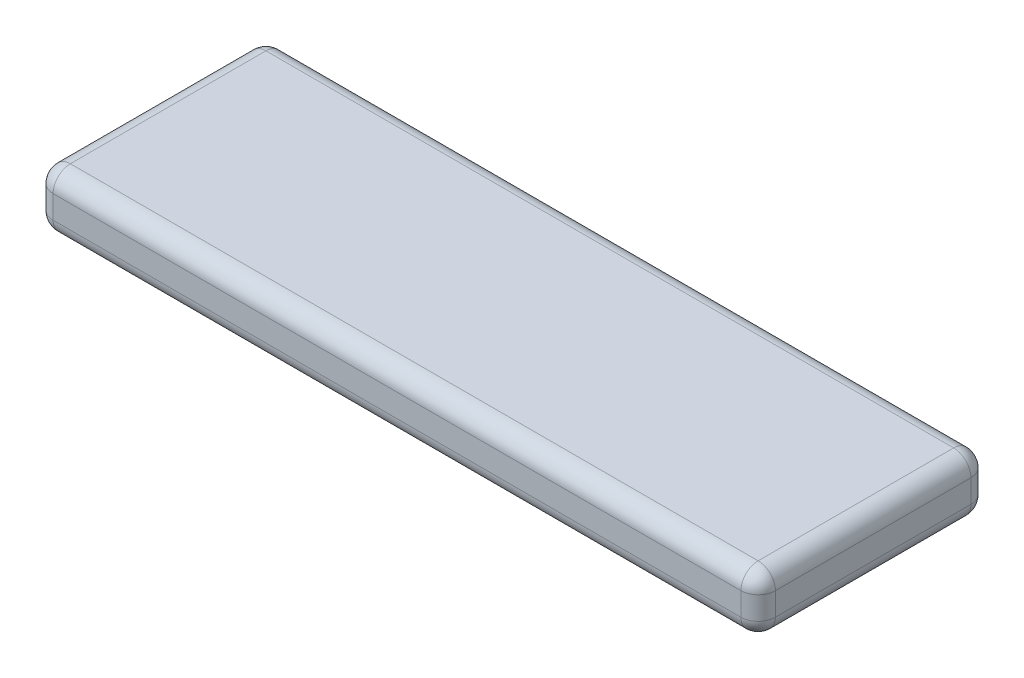
SolidWorks part; units mm, degrees
ref_plane "Front Plane" through (0, 0, 0) normal (0, 0, 1) x (1, 0, 0)
ref_plane "Top Plane" through (0, 0, 0) normal (0, 1, 0) x (1, 0, 0)
ref_plane "Right Plane" through (0, 0, 0) normal (1, 0, 0) x (0, 0, -1)
sketch "Sketch1" plane through (0, 0, 0) normal (0, 1, 0) x (1, 0, 0)
  line L1 (0, 0) -> (1256, 0)
  line L2 (0, 0) -> (0, 400)
  line L3 (0, 400) -> (1256, 400)
  line L4 (1256, 0) -> (1256, 400)
  dimension "D1" = 1256
  dimension "D2" = 400
extrude "Boss-Extrude1" add sketch "Sketch1" along normal blind 100
fillet "Fillet1" radius 30 12 edges at (0, 0, -200) (0, 50, -400) (628, 0, -400) (0, 50, 0) (1256, 50, 0) (1256, 50, -400) (628, 100, -400) (1256, 100, -200) (628, 100, 0) (0, 100, -200) (1256, 0, -200) (628, 0, 0)
equation "\"length\"=1256"
equation "\"D1@Sketch1\"=\"length\""
equation "\"height\"= 400"
